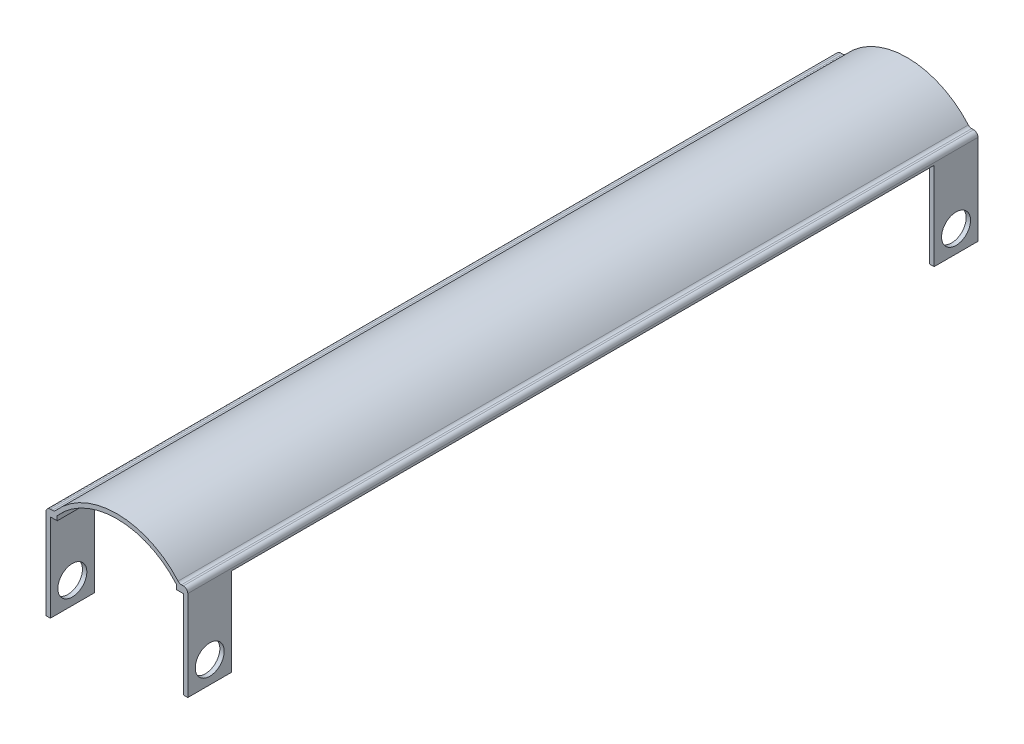
SolidWorks part; units mm, degrees
ref_plane "Ebene vorne" through (0, 0, 0) normal (0, 0, 1) x (1, 0, 0)
ref_plane "Ebene oben" through (0, 0, 0) normal (0, 1, 0) x (1, 0, 0)
ref_plane "Ebene rechts" through (0, 0, 0) normal (1, 0, 0) x (0, 0, -1)
sketch "Skizze1" plane through (0, 0, 0) normal (0, 0, 1) x (1, 0, 0)
  line L0 (0, 0) -> (0, 50000) construction
  line L1 (-16.15, 0) -> (-14.231, 0)
  line L2 (-1000, 0) -> (-14.231, 0) construction
  line L3 (15, -1.522) -> (15.15, -1.522)
  line L6 (-13.5937, -0.522) -> (-13.5937, -1.522)
  line L7 (13.5937, -0.522) -> (13.5937, -1.522)
  line L8 (-13.5937, -1.522) -> (-15, -1.522)
  line L9 (15.15, -1.522) -> (15.15, -21.522)
  line L10 (13.5937, -1.522) -> (15, -1.522)
  line L11 (14.231, 0) -> (50000, 0) construction
  line L12 (15.15, -21.522) -> (16.15, -21.522)
  line L13 (-15, -1.522) -> (-15.15, -1.522)
  line L14 (-15.15, -1.522) -> (-15.15, -21.522)
  line L15 (-15.15, -21.522) -> (-16.15, -21.522)
  line L16 (-16.15, -21.522) -> (-16.15, 0)
  line L18 (16.15, -21.522) -> (16.15, 0)
  line L19 (16.15, 0) -> (14.231, 0)
  arc A1 (-13.5937, -0.522) -> (13.5937, -0.522) centre (0, -12.3207) cw
  arc A3 (-14.231, 0) -> (14.231, 0) centre (0, -11.8207) cw
  dimension "D3" = 18
  dimension "D12" = 30.3
  dimension "D4" = 0.5
  dimension "D13" = 18.5
  dimension "D2" = 1.4062
  dimension "D5" = 1
  dimension "D6" = 0.15
  dimension "D7" = 20
  dimension "D8" = 1
  dimension "D9" = 0.15
  dimension "D10" = 1
  dimension "D11" = 1.4062
extrude "Aufsatz-Linear austragen1" add sketch "Skizze1" along normal blind 180
hole_wizard "Durchgangsloch für M61" positions "Skizze2" profile "Skizze3" hole size "M6" standard "DIN" end condition through all
sketch "Skizze2" plane through (-16.15, 0, 0) normal (1, 0, 0) x (0, 0, -1)
  line L0 (0, -21.522) -> (0, 0) construction
  line L2 (-180, -1.522) -> (0, -1.522) construction
  point P1 (-5, -16.522)
  dimension "D1" = 5
  dimension "D2" = 15
sketch "Skizze3" plane through (-16.15, -16.522, 5) normal (0, 1, 0) x (0, 0, 1)
  line L0 (0, 0) -> (0, 32.3)
  line L1 (0, 32.3) -> (3.3, 32.3)
  line L2 (3.3, 32.3) -> (3.3, 0)
  line L5 (3.3, 0) -> (0, 0)
  line L11 (0, -6.35) -> (0, 107.95) construction
  dimension "Bohrerdurchmesser" = 6.6
  dimension "Bohrungstiefe" = 32.3
ref_plane "Ebene1" through (0, 0, 90) normal (0, 0, 1) x (1, 0, 0)
mirror "Spiegeln1" about plane through (0, 0, 90) normal (0, 0, 1) of "Durchgangsloch für M61"
sketch "Skizze4" plane through (16.15, 0, 0) normal (1, 0, 0) x (0, 0, -1)
  line L0 (-10, -21.522) -> (-10, -1.522)
  line L1 (-170, -21.522) -> (-170, -1.522)
  line L2 (-180, -21.522) -> (0, -21.522) construction
  line L3 (-90, 15.5107) -> (-90, -15.5107) construction
  line L4 (-180, -1.522) -> (0, -1.522) construction
  line L5 (-170, -1.522) -> (-10, -1.522)
  line L7 (-10, -21.522) -> (-170, -21.522)
  dimension "D1" = 80
extrude "Schnitt-Linear austragen1" cut sketch "Skizze4" against normal through all
fillet "Verrundung1" radius 1 4 edges at (-16.15, 0, 90) (16.15, 0, 90) (14.231, 0, 90) (-14.231, 0, 90)
